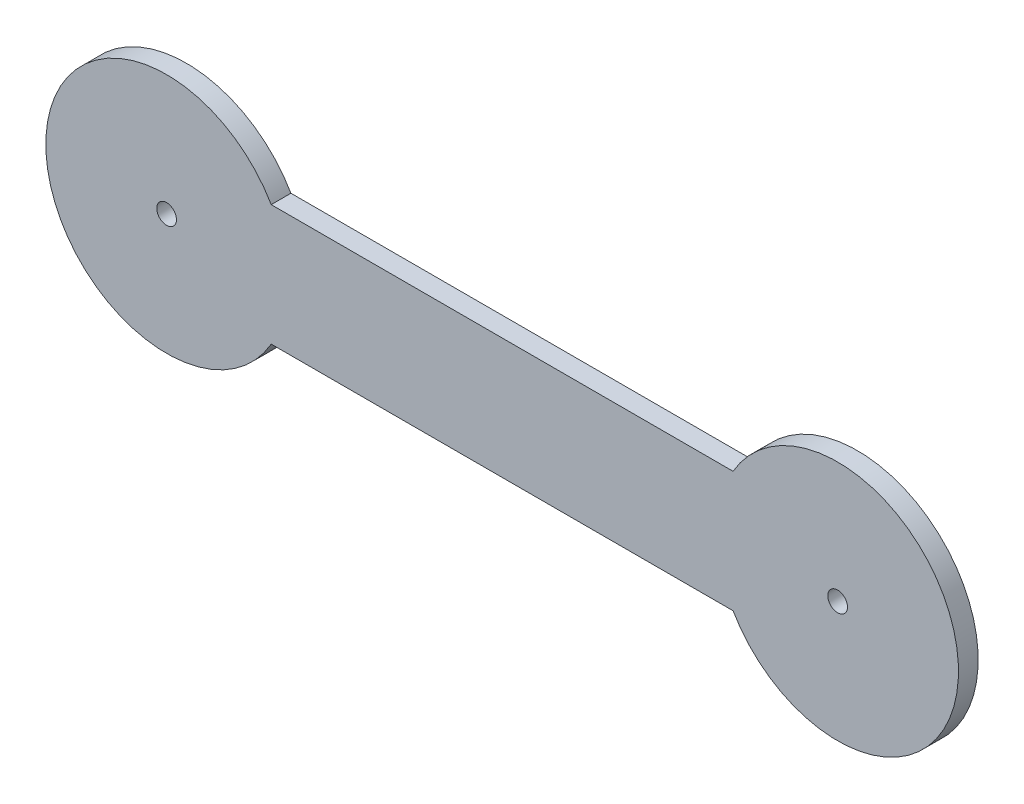
SolidWorks part; units mm, degrees
ref_plane "Front Plane" through (0, 0, 0) normal (0, 0, 1) x (1, 0, 0)
ref_plane "Top Plane" through (0, 0, 0) normal (0, 1, 0) x (1, 0, 0)
ref_plane "Right Plane" through (0, 0, 0) normal (1, 0, 0) x (0, 0, -1)
sketch "Sketch1" plane through (0, 0, 0) normal (0, 0, 1) x (1, 0, 0)
  line L1 (0, 0) -> (211.6667, 0)
  line L2 (0, 0) -> (0, 38.1)
  line L3 (0, 38.1) -> (211.6667, 38.1)
  line L4 (211.6667, 0) -> (211.6667, 38.1)
  circle A0 centre (0, 19.05) radius 3.1115
  circle A1 centre (211.6667, 19.05) radius 3.1115
  circle A2 centre (0, 19.05) radius 38.1
  circle A3 centre (211.6667, 19.05) radius 38.1
  dimension "D3" = 6.223
  dimension "D4" = 6.223
  dimension "D5" = 76.2
  dimension "D6" = 76.2
  dimension "D1" = 211.6667
  dimension "D2" = 38.1
extrude "Boss-Extrude1" add sketch "Sketch1" along normal blind 6.223 contours L3 A2 L1 L2 A0 | L1 A2 L3 L2 A0 | A3 L3 A2 L1 | L3 A3 L1 L4 A1 | L1 A3 L3 L4 A1
